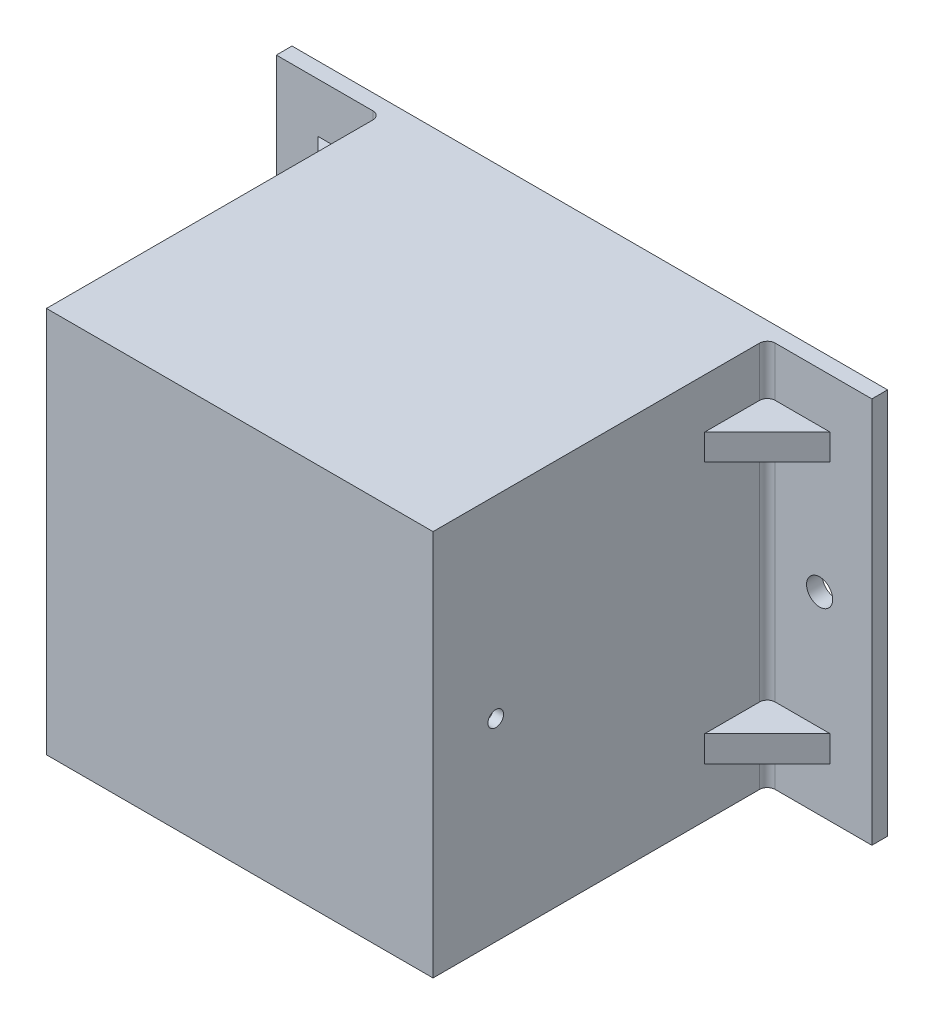
SolidWorks part; units mm, degrees
ref_plane "前视基准面" through (0, 0, 0) normal (0, 0, 1) x (1, 0, 0)
ref_plane "上视基准面" through (0, 0, 0) normal (0, 1, 0) x (1, 0, 0)
ref_plane "右视基准面" through (0, 0, 0) normal (1, 0, 0) x (0, 0, -1)
sketch "草图1" plane through (0, 0, 0) normal (0, 0, 1) x (1, 0, 0)
  line L1 (-35, 35) -> (35, 35)
  line L2 (-35, 35) -> (-35, -35)
  line L3 (-35, -35) -> (35, -35)
  line L4 (35, 35) -> (35, -35)
  line L5 (0, -35) -> (0, 35) construction
  line L6 (-35, 0) -> (35, 0) construction
  line L7 (-37, 37) -> (37, 37)
  line L8 (-37, 37) -> (-37, -37)
  line L9 (-37, -37) -> (37, -37)
  line L10 (37, 37) -> (37, -37)
  line L11 (0, -37) -> (0, 37) construction
  line L12 (-37, 0) -> (37, 0) construction
  point P0 (0, 0)
  point P4 (0, 0)
  dimension "D1" = 70
  dimension "D2" = 70
  dimension "D3" = 2
  dimension "D4" = 2
extrude "凸台-拉伸1" add sketch "草图1" along normal blind 65
sketch "草图2" plane through (0, 0, 65) normal (0, 0, 1) x (1, 0, 0)
  line L1 (-37, 37) -> (37, 37)
  line L2 (-37, 37) -> (-37, -37)
  line L3 (-37, -37) -> (37, -37)
  line L4 (37, 37) -> (37, -37)
  line L5 (0, -37) -> (0, 37) construction
  line L6 (-37, 0) -> (37, 0) construction
  point P0 (0, 0)
extrude "凸台-拉伸2" add sketch "草图2" along normal blind 2
sketch "草图3" plane through (0, 0, 0) normal (0, 0, -1) x (-1, 0, 0)
  line L1 (-57, 37) -> (-37, 37)
  line L2 (-57, 37) -> (-57, -37)
  line L3 (-57, -37) -> (-37, -37)
  line L4 (57, 37) -> (57, -37)
  line L5 (0, -37) -> (0, 37) construction
  line L6 (-57, 0) -> (-37, 0) construction
  line L8 (37, 37) -> (37, -37) construction
  line L9 (37, 37) -> (57, 37)
  line L11 (-37, -37) -> (-37, 37)
  line L13 (37, -37) -> (37, 37)
  line L14 (0, 37) -> (0, -37) construction
  line L16 (37, 0) -> (57, 0) construction
  line L17 (37, -37) -> (57, -37)
  point P0 (0, 0)
  point P6 (0, 0)
  dimension "D2" = 20
extrude "凸台-拉伸3" add sketch "草图3" against normal blind 3
ref_plane "基准面1" through (0, 25, 0) normal (0, 1, 0) x (1, 0, 0)
ref_plane "基准面2" through (0, -25, 0) normal (0, 1, 0) x (1, 0, 0)
sketch "草图4" plane through (0, 25, 0) normal (0, 1, 0) x (1, 0, 0)
  line L0 (-37, -15) -> (-49, -3)
  line L1 (-37, -67) -> (-37, -3) construction
  line L2 (-57, -3) -> (-37, -3) construction
  line L3 (-49, -3) -> (-37, -3)
  line L4 (-37, -3) -> (-37, -15)
  dimension "D1" = 12
extrude "凸台-拉伸4" add sketch "草图4" along normal mid plane 5
sketch "草图5" plane through (0, -25, 0) normal (0, 1, 0) x (1, 0, 0)
  line L3 (-37, -15) -> (-37, -3)
  line L4 (-37, -3) -> (-49, -3)
  line L5 (-49, -3) -> (-37, -15)
  line L6 (-37, -15) -> (-37, -3)
  line L7 (-37, -3) -> (-49, -3)
  line L8 (-49, -3) -> (-37, -15)
  dimension "D1" = 0
extrude "凸台-拉伸5" add sketch "草图5" along normal mid plane 5
mirror "镜向1" about plane through (0, 0, 0) normal (1, 0, 0) of "凸台-拉伸5", "凸台-拉伸4"
sketch "草图6" plane through (0, 0, 3) normal (0, 0, 1) x (1, 0, 0)
  line L0 (0, 0) -> (0, 18.5204) construction
  line L1 (37, 37) -> (57, 37) construction
  circle A0 centre (47, 0) radius 2.5
  circle A1 centre (-47, 0) radius 2.5
  point P5 (0, 0)
  point P6 (0, 0)
  point P9 (47, 37)
  point P12 (-47, 37)
  dimension "D2" = 5
  dimension "D1" = 18.5204
extrude "切除-拉伸1" cut sketch "草图6" against normal blind 5
fillet "圆角1" radius 1.5 6 edges at (-37, 0, 3) (37, -32.25, 3) (37, 0, 3) (37, 32.25, 3) (-37, 32.25, 3) (-37, -32.25, 3)
sketch "草图7" plane through (0, -37, 0) normal (0, -1, 0) x (1, 0, 0)
  line L0 (-4, 0) -> (-4, 50)
  line L1 (-57, 0) -> (57, 0) construction
  line L2 (-4, 50) -> (4, 50)
  line L3 (4, 50) -> (4, 0)
  line L4 (4, 0) -> (-4, 0)
  point P4 (0, 50)
  dimension "D1" = 50
  dimension "D2" = 8
extrude "切除-拉伸2" cut sketch "草图7" against normal blind 5
sketch "草图9" plane through (37, 0, 0) normal (1, 0, 0) x (0, 0, -1)
  circle A0 centre (-55, 0) radius 1.5
  dimension "D1" = 3
  dimension "D2" = 55
extrude "切除-拉伸3" cut sketch "草图9" against normal blind 5
